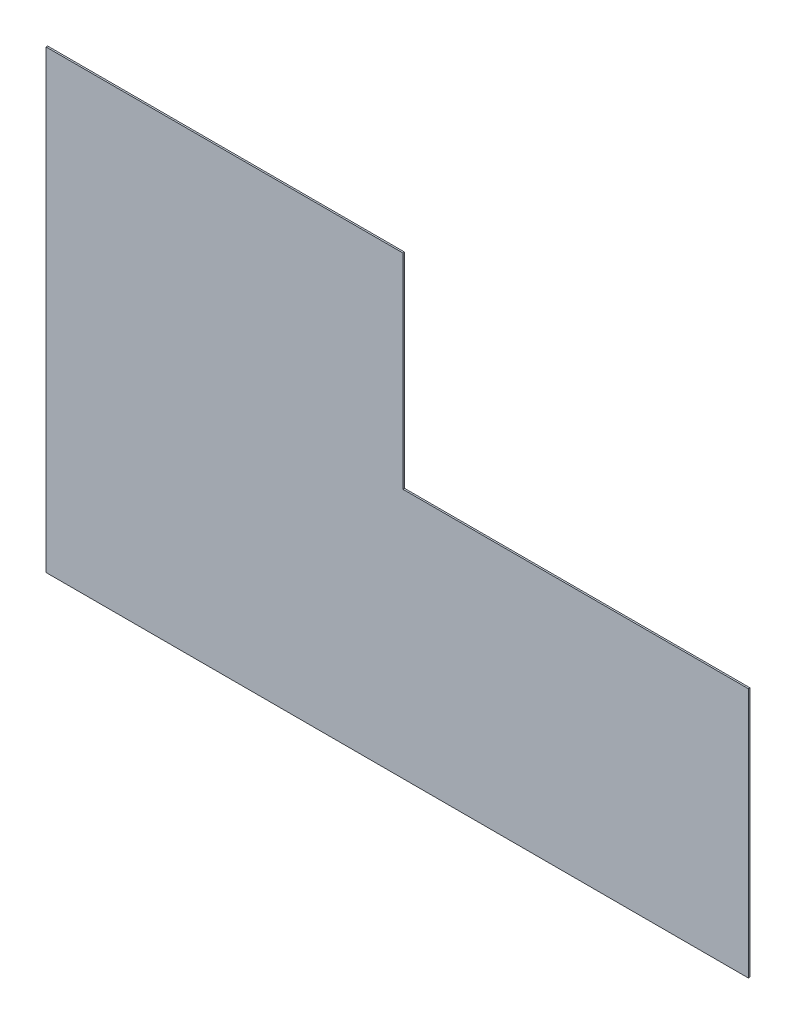
SolidWorks part; units mm, degrees
material "Acrylic (Medium-high impact)"
ref_plane "Front Plane" through (0, 0, 0) normal (0, 0, 1) x (1, 0, 0)
ref_plane "Top Plane" through (0, 0, 0) normal (0, 1, 0) x (1, 0, 0)
ref_plane "Right Plane" through (0, 0, 0) normal (1, 0, 0) x (0, 0, -1)
sketch "Sketch1" plane through (0, 0, 0) normal (0, 0, 1) x (1, 0, 0)
  line L0 (0, 244.6657) -> (-337.207, 244.6657)
  line L1 (0, 0) -> (-685.8, 0)
  line L2 (0, 0) -> (0, 244.6657)
  line L3 (-337.207, 444.5) -> (-685.8, 444.5)
  line L4 (-685.8, 0) -> (-685.8, 444.5)
  line L5 (9.1459, 244.6657) -> (-92.4541, 244.6657) construction
  line L6 (-337.207, 244.6657) -> (-337.207, 444.5)
  dimension "D1" = 685.8
  dimension "D2" = 444.5
extrude "Boss-Extrude1" add sketch "Sketch1" along normal blind 1.5875
